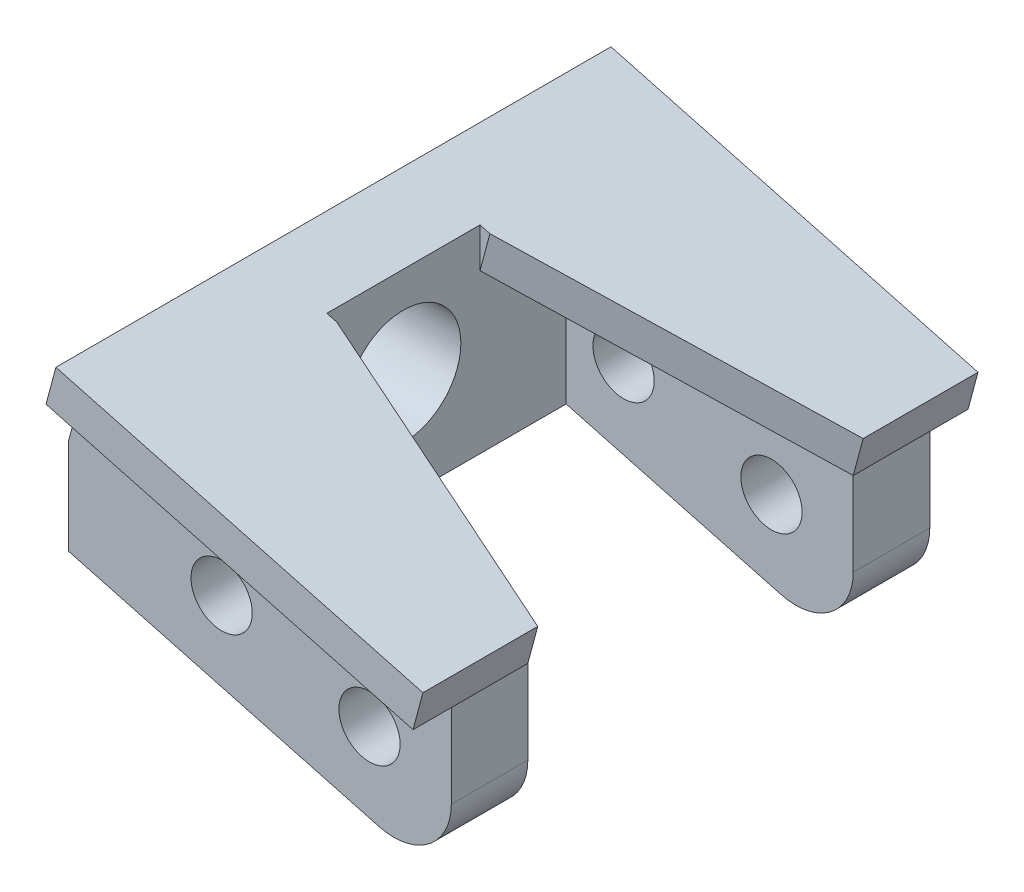
SolidWorks part; units mm, degrees
material "POM 乙缩醛共聚物"
ref_plane "前视基准面" through (0, 0, 0) normal (0, 0, 1) x (1, 0, 0)
ref_plane "上视基准面" through (0, 0, 0) normal (0, 1, 0) x (1, 0, 0)
ref_plane "右视基准面" through (0, 0, 0) normal (1, 0, 0) x (0, 0, -1)
sketch "草图1" plane through (0, 0, 0) normal (1, 0, 0) x (0, 0, -1)
  line L0 (0, 0) -> (0, 1.5) construction
  line L1 (12.5, -5.5) -> (-12.5, -5.5)
  line L2 (12.5, -5.5) -> (12.5, 5.5)
  line L3 (12.5, 5.5) -> (-12.5, 5.5)
  line L4 (-12.5, -5.5) -> (-12.5, 5.5)
  line L5 (12.5, -5.5) -> (-12.5, 5.5) construction
  line L6 (12.5, 5.5) -> (-12.5, -5.5) construction
  point P0 (0, 0)
  dimension "D2" = 11
  dimension "D3" = 25
  dimension "D4" = 1.5
extrude "凸台-拉伸1" add sketch "草图1" along normal blind 5
sketch "草图2" plane through (5, 0, 0) normal (1, 0, 0) x (0, 0, -1)
  line L0 (0, 0) -> (0, 6.4242) construction
  line L1 (-8.5, -9.5) -> (-12.5, -9.5)
  line L2 (-8.5, -9.5) -> (-8.5, 5.5)
  line L3 (-8.5, 5.5) -> (-12.5, 5.5)
  line L4 (-12.5, -9.5) -> (-12.5, 5.5)
  line L5 (-8.5, -9.5) -> (-12.5, 5.5) construction
  line L6 (-8.5, 5.5) -> (-12.5, -9.5) construction
  line L7 (8.5, 5.5) -> (12.5, 5.5)
  line L8 (12.5, -9.5) -> (12.5, 5.5)
  line L9 (8.5, -9.5) -> (12.5, -9.5)
  line L10 (8.5, -9.5) -> (8.5, 5.5)
  line L11 (-12.5, -5.5) -> (12.5, -5.5) construction
  point P0 (-10.5, -2)
  dimension "D1" = 4
  dimension "D2" = 4
extrude "凸台-拉伸2" add sketch "草图2" along normal blind 15
sketch "草图4" plane through (0, 0, 12.5) normal (0, 0, 1) x (1, 0, 0)
  line L0 (20, -4.0001) -> (0, 1.3589) construction
  line L1 (20, 5.5) -> (20, -9.5) construction
  line L2 (0, 5.5) -> (0, -5.5) construction
  line L3 (20, 5.5) -> (0, 5.5) construction
  line L4 (0, 5.5) -> (20, 0.141)
  line L5 (20, 5.5) -> (20, -9.5) construction
  line L6 (0, -2.7822) -> (20, -8.1412)
  line L7 (20, -8.1412) -> (20, -9.5)
  line L8 (20, -9.5) -> (0, -9.5)
  line L9 (0, -9.5) -> (0, -2.7822)
  line L10 (20, 0.141) -> (20, 5.5)
  line L11 (20, 5.5) -> (0, 5.5)
  circle A0 centre (15.7274, -2.8553) radius 1.6
  circle A1 centre (8, -0.7847) radius 1.6
  dimension "D4" = 3.2
  dimension "D1" = 4
  dimension "D2" = 8
  dimension "D3" = 8
  dimension "D5" = 15
  dimension "D6" = 4
extrude "切除-拉伸1" cut sketch "草图4" against normal through all
sketch "草图6" plane through (1.375, 5.1316, 0) normal (0.2588, 0.9659, 0) x (0.9659, -0.2588, 0)
  line L0 (19.282, 8.5) -> (19.282, 14.5)
  line L1 (19.282, 14.5) -> (-1.4235, 14.5)
  line L2 (-1.4235, 14.5) -> (-1.4235, -14.5)
  line L3 (-1.4235, 12.5) -> (-1.4235, -12.5) construction
  line L4 (19.282, 8.5) -> (3.7529, 4)
  line L5 (3.7529, -8.5) -> (3.7529, 8.5) construction
  line L6 (3.7529, 4) -> (3.7529, -4)
  line L7 (19.282, 8.5) -> (3.7529, 8.5) construction
  line L8 (-1.4235, 12.5) -> (19.282, 12.5) construction
  line L9 (-1.4235, 0) -> (1.9745, 0) construction
  line L10 (19.282, -8.5) -> (3.7529, -4)
  line L11 (19.282, -14.5) -> (-1.4235, -14.5)
  line L12 (19.282, -8.5) -> (19.282, -14.5)
  point P18 (3.7529, 0)
  dimension "D1" = 4.5
  dimension "D2" = 2
extrude "凸台-拉伸3" add sketch "草图6" along normal blind 2
sketch "草图7" plane through (0, 0, 14.5) normal (0, 0, 1) x (1, 0, 0)
  line L0 (1.3425, 7.2108) -> (0, 2.2004)
  line L5 (0.5176, 7.4319) -> (20.5176, 2.0729) construction
  line L6 (0, 5.5) -> (0, -2.7822) construction
  line L7 (0, 2.2004) -> (-7.1797, 0.6537)
  line L8 (-7.1797, 0.6537) -> (-4.4821, 8.7715)
  line L9 (-4.4821, 8.7715) -> (1.3425, 7.2108)
  circle A0 centre (8, -0.7847) radius 1.6 construction
  dimension "D1" = 8.5
extrude "切除-拉伸2" cut sketch "草图7" against normal through all
sketch "草图8" plane through (5, 0, 0) normal (1, 0, 0) x (0, 0, -1)
  line L0 (8.5, -4.122) -> (-8.5, -4.122) construction
  circle A0 centre (0, 1.378) radius 3
  dimension "D1" = 6
  dimension "D2" = 5.5
extrude "切除-拉伸3" cut sketch "草图8" against normal through all
sketch "草图9" plane through (5, 0, 0) normal (1, 0, 0) x (0, 0, -1)
  line L0 (4, 6.7499) -> (4, 0.486)
  line L1 (4, 0.486) -> (-4, 0.486)
  line L2 (-4, 0.486) -> (-4, 6.7499)
  line L3 (-4, 6.7499) -> (4, 6.7499)
extrude "切除-拉伸4" cut sketch "草图9" along normal through all
fillet "圆角1" radius 3 2 edges at (20, -8.1412, -10.5) (20, -8.1412, 10.5)
